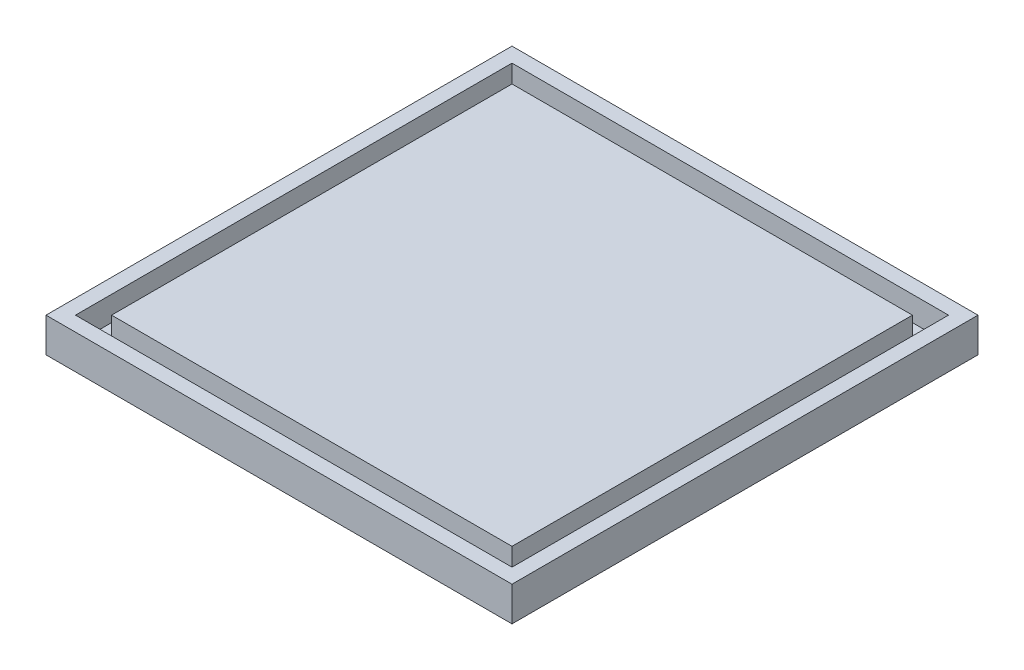
SolidWorks part; units mm, degrees
ref_plane "Front Plane" through (0, 0, 0) normal (0, 0, 1) x (1, 0, 0)
ref_plane "Top Plane" through (0, 0, 0) normal (0, 1, 0) x (1, 0, 0)
ref_plane "Right Plane" through (0, 0, 0) normal (1, 0, 0) x (0, 0, -1)
sketch "Sketch1" plane through (0, 0, 0) normal (0, 1, 0) x (1, 0, 0)
  line L0 (0, 81.5) -> (0, 85.175) construction
  line L1 (0, 0) -> (81.5, 0)
  line L2 (0, 0) -> (0, 81.5)
  line L3 (0, 81.5) -> (81.5, 81.5)
  line L4 (81.5, 0) -> (81.5, 81.5)
  line L5 (-3.675, 85.175) -> (85.175, 85.175)
  line L6 (-3.675, 85.175) -> (-3.675, -3.675)
  line L7 (-3.675, -3.675) -> (85.175, -3.675)
  line L8 (85.175, 85.175) -> (85.175, -3.675)
  line L9 (88.175, -6.675) -> (-6.675, -6.675)
  line L10 (88.175, -6.675) -> (88.175, 88.175)
  line L11 (88.175, 88.175) -> (-6.675, 88.175)
  line L12 (-6.675, -6.675) -> (-6.675, 88.175)
  line L13 (0, 81.5) -> (-3.675, 81.5) construction
  line L14 (-3.675, 85.175) -> (-3.675, 88.175) construction
  line L15 (-3.675, 85.175) -> (-6.675, 85.175) construction
  line L16 (81.5, 0) -> (85.175, 0) construction
  line L17 (81.5, 0) -> (81.5, -3.675) construction
  line L18 (85.175, -3.675) -> (85.175, -6.675) construction
  line L19 (85.175, -3.675) -> (88.175, -3.675) construction
  point P18 (98.6629, -20.5284)
  dimension "D1" = 81.5
  dimension "D2" = 3
  dimension "D3" = 3.675
extrude "Boss-Extrude1" add sketch "Sketch1" along normal blind 5 contours L12 L9 L10 L11 L5 L8 L7 L6 | L1 L4 L3 L2
sketch "Sketch2" plane through (0, 0, 0) normal (0, -1, 0) x (1, 0, 0)
  line L1 (-6.675, 6.675) -> (88.175, 6.675)
  line L2 (-6.675, 6.675) -> (-6.675, -88.175)
  line L3 (-6.675, -88.175) -> (88.175, -88.175)
  line L4 (88.175, 6.675) -> (88.175, -88.175)
extrude "Boss-Extrude2" add sketch "Sketch2" along normal blind 2
